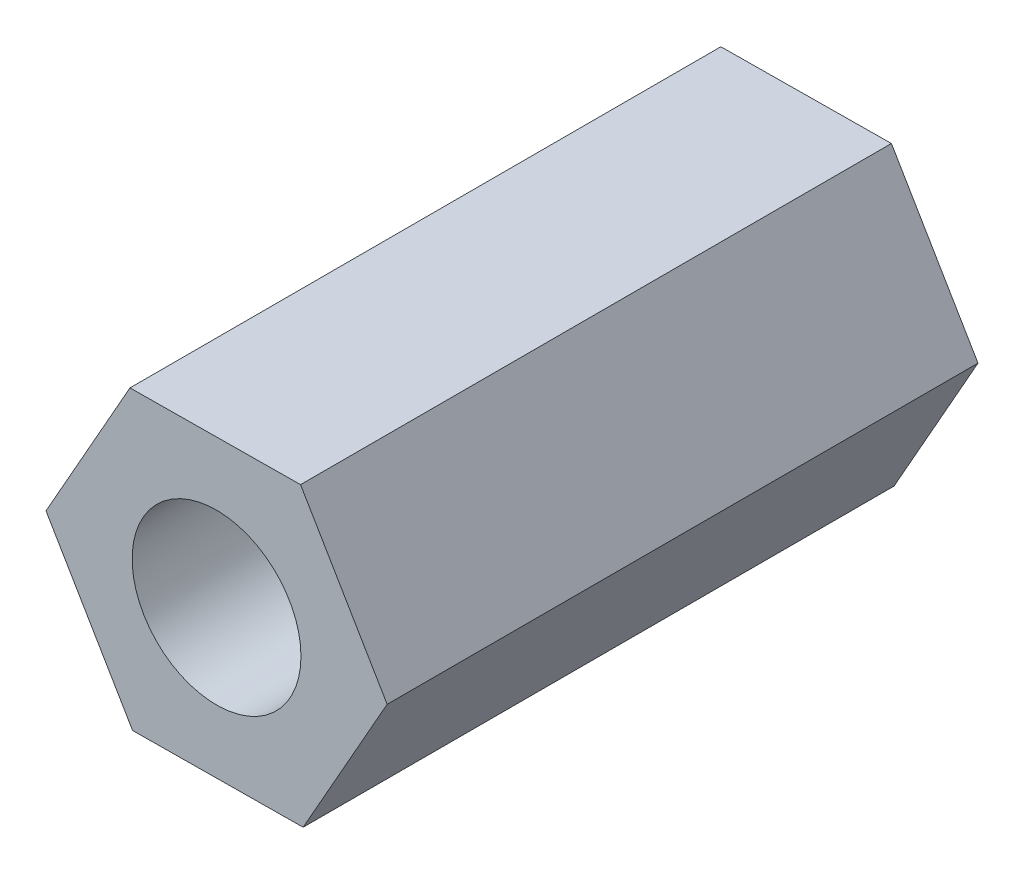
SolidWorks part; units mm, degrees
ref_plane "前视基准面" through (0, 0, 0) normal (0, 0, 1) x (1, 0, 0)
ref_plane "上视基准面" through (0, 0, 0) normal (0, 1, 0) x (1, 0, 0)
ref_plane "右视基准面" through (0, 0, 0) normal (1, 0, 0) x (0, 0, -1)
sketch "草图1" plane through (0, 0, 0) normal (0, 0, 1) x (1, 0, 0)
  line L1 (2.0515, -3.4821) -> (4.0413, 0.0356)
  line L2 (4.0413, 0.0356) -> (1.9898, 3.5177)
  line L3 (1.9898, 3.5177) -> (-2.0515, 3.4821)
  line L4 (-2.0515, 3.4821) -> (-4.0413, -0.0356)
  line L5 (-4.0413, -0.0356) -> (-1.9898, -3.5177)
  line L6 (-1.9898, -3.5177) -> (2.0515, -3.4821)
  circle A0 centre (0, 0) radius 3.5 construction
  circle A1 centre (0, 0) radius 2
extrude "凸台-拉伸1" add sketch "草图1" along normal blind 14
